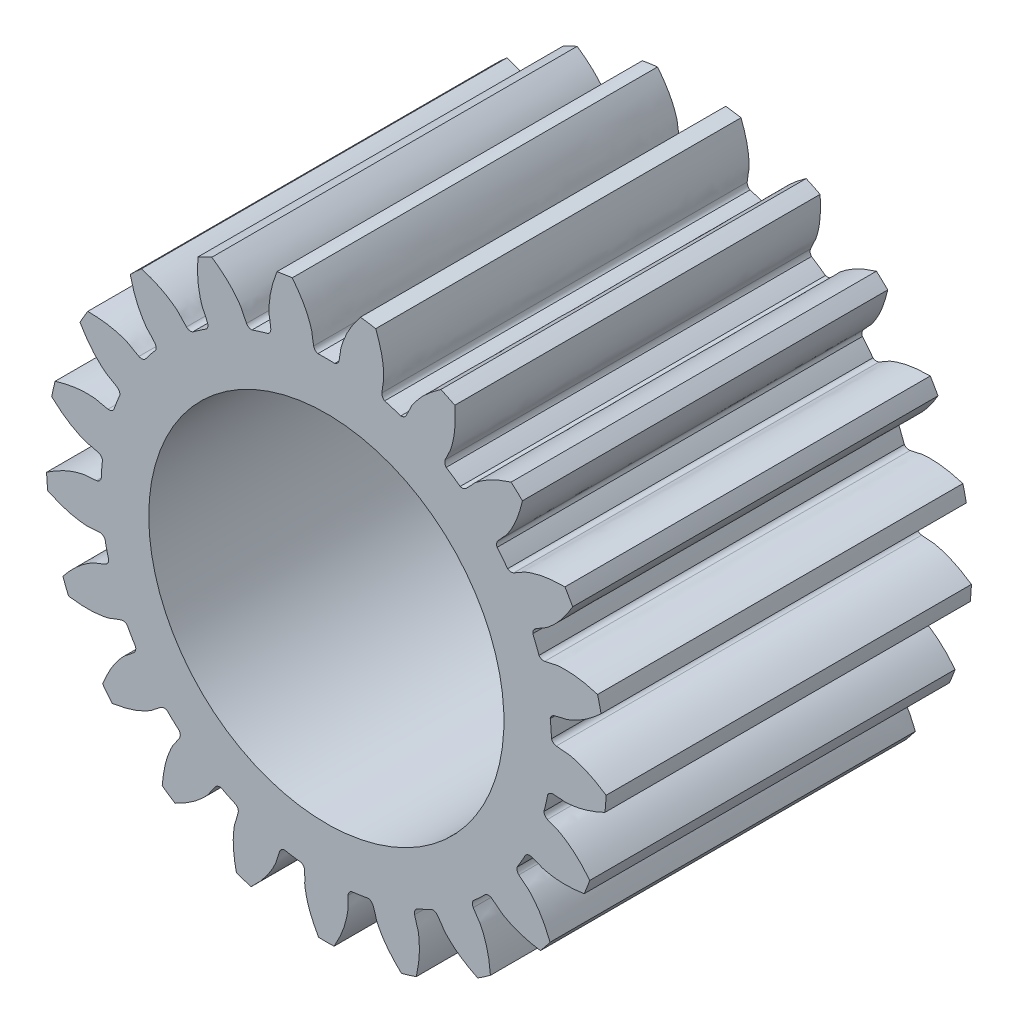
SolidWorks part; units mm, degrees
ref_plane "Front Plane" through (0, 0, 0) normal (0, 0, 1) x (1, 0, 0)
ref_plane "Top Plane" through (0, 0, 0) normal (0, 1, 0) x (1, 0, 0)
ref_plane "Right Plane" through (0, 0, 0) normal (1, 0, 0) x (0, 0, -1)
ref_plane "Plane1" through (0, 0, 19) normal (0, 0, 1) x (1, 0, 0)
sketch "Sketch1" plane through (0, 0, 19) normal (0, 0, 1) x (1, 0, 0)
  arc A0 (6.1126, 17.461) -> (4.7856, 17.8703) centre (0, 0) ccw
  arc A1 (4.7856, 17.8703) -> (4.5626, 18.3266) centre (5.0611, 18.2876) cw
  arc A2 (4.0545, 22.6398) -> (2.7989, 22.8291) centre (0, 0) ccw
  arc A3 (1.042, 18.8573) -> (0.6944, 18.487) centre (0.5542, 18.9669) cw
  arc A4 (0.6944, 18.487) -> (-0.6944, 18.487) centre (0, 0) ccw
  arc A5 (-0.6944, 18.487) -> (-1.042, 18.8573) centre (-0.5542, 18.9669) cw
  arc A6 (-2.7989, 22.8291) -> (-4.0545, 22.6398) centre (0, 0) ccw
  arc A7 (-4.5626, 18.3266) -> (-4.7856, 17.8703) centre (-5.0611, 18.2876) cw
  arc A8 (-4.7856, 17.8703) -> (-6.1126, 17.461) centre (0, 0) ccw
  arc A9 (-6.1126, 17.461) -> (-6.554, 17.7124) centre (-6.1201, 17.9609) cw
  arc A10 (-9.4035, 20.9899) -> (-10.5476, 20.4389) centre (0, 0) ccw
  arc A11 (-9.7617, 16.1676) -> (-9.8404, 15.6658) centre (-10.2266, 15.9834) cw
  arc A12 (-9.8404, 15.6658) -> (-10.9878, 14.8835) centre (0, 0) ccw
  arc A13 (-10.9878, 14.8835) -> (-11.4836, 14.9936) centre (-11.1423, 15.359) cw
  arc A14 (-15.1726, 17.2856) -> (-16.1034, 16.4219) centre (0, 0) ccw
  arc A15 (-14.0935, 12.572) -> (-14.0208, 12.0693) centre (-14.4834, 12.2589) cw
  arc A16 (-14.0208, 12.0693) -> (-14.8866, 10.9836) centre (0, 0) ccw
  arc A17 (-14.8866, 10.9836) -> (-15.3929, 10.9427) centre (-15.1744, 11.3924) cw
  arc A18 (-19.5935, 12.0455) -> (-20.2284, 10.9458) centre (0, 0) ccw
  arc A19 (-17.1731, 7.8593) -> (-16.9554, 7.4004) centre (-17.4533, 7.4452) cw
  arc A20 (-16.9554, 7.4004) -> (-17.4627, 6.1077) centre (0, 0) ccw
  arc A21 (-17.4627, 6.1077) -> (-17.9344, 5.9194) centre (-17.8583, 6.4135) cw
  arc A22 (-22.2735, 5.735) -> (-22.5561, 4.497) centre (0, 0) ccw
  arc A23 (-18.7267, 2.4483) -> (-18.3834, 2.074) centre (-18.8725, 1.97) cw
  arc A24 (-18.3834, 2.074) -> (-18.4872, 0.6891) centre (0, 0) ccw
  arc A25 (-18.4872, 0.6891) -> (-18.8824, 0.3701) centre (-18.9553, 0.8648) cw
  arc A26 (-22.9744, -1.085) -> (-22.8795, -2.3513) centre (0, 0) ccw
  arc A27 (-18.6164, -3.1803) -> (-18.178, -3.4368) centre (-18.6147, -3.6803) cw
  arc A28 (-18.178, -3.4368) -> (-17.8689, -4.7907) centre (0, 0) ccw
  arc A29 (-17.8689, -4.7907) -> (-18.1526, -5.212) centre (-18.3681, -4.7608) cw
  arc A30 (-21.6339, -7.8086) -> (-21.17, -8.9907) centre (0, 0) ccw
  arc A31 (-16.8519, -8.5262) -> (-16.3574, -8.6421) centre (-16.7029, -9.0035) cw
  arc A32 (-16.3574, -8.6421) -> (-15.663, -9.8448) centre (0, 0) ccw
  arc A33 (-15.663, -9.8448) -> (-15.8099, -10.331) centre (-16.1487, -9.9634) cw
  arc A34 (-18.3711, -13.8384) -> (-17.5794, -14.8312) centre (0, 0) ccw
  arc A35 (-13.5901, -13.1146) -> (-13.0833, -13.0796) centre (-13.307, -13.5268) cw
  arc A36 (-13.0833, -13.0796) -> (-12.0653, -14.0242) centre (0, 0) ccw
  arc A37 (-12.0653, -14.0242) -> (-12.0624, -14.5321) centre (-12.4945, -14.2807) cw
  arc A38 (-13.476, -18.6386) -> (-12.4268, -19.3539) centre (0, 0) ccw
  arc A39 (-9.1207, -16.5377) -> (-8.6468, -16.3549) centre (-8.7287, -16.8481) cw
  arc A40 (-8.6468, -16.3549) -> (-7.3956, -16.9575) centre (0, 0) ccw
  arc A41 (-7.3956, -16.9575) -> (-7.2431, -17.4419) centre (-7.7301, -17.329) cw
  arc A42 (-7.3835, -21.7827) -> (-6.1701, -22.1569) centre (0, 0) ccw
  arc A43 (-3.8409, -18.4914) -> (-3.4419, -18.177) centre (-3.3748, -18.6725) cw
  arc A44 (-3.4419, -18.177) -> (-2.0687, -18.384) centre (0, 0) ccw
  arc A45 (-2.0687, -18.384) -> (-1.7802, -18.802) centre (-2.2789, -18.8377) cw
  arc A46 (-0.6349, -22.9912) -> (0.6349, -22.9912) centre (0, 0) ccw
  arc A47 (1.7802, -18.802) -> (2.0687, -18.384) centre (2.2789, -18.8377) cw
  arc A48 (2.0687, -18.384) -> (3.4419, -18.177) centre (0, 0) ccw
  arc A49 (3.4419, -18.177) -> (3.8409, -18.4914) centre (3.3748, -18.6725) cw
  arc A50 (6.1701, -22.1569) -> (7.3835, -21.7827) centre (0, 0) ccw
  arc A51 (7.2431, -17.4419) -> (7.3956, -16.9575) centre (7.7301, -17.329) cw
  arc A52 (7.3956, -16.9575) -> (8.6468, -16.3549) centre (0, 0) ccw
  arc A53 (8.6468, -16.3549) -> (9.1207, -16.5377) centre (8.7287, -16.8481) cw
  arc A54 (12.4268, -19.3539) -> (13.476, -18.6386) centre (0, 0) ccw
  arc A55 (12.0624, -14.5321) -> (12.0653, -14.0242) centre (12.4945, -14.2807) cw
  arc A56 (12.0653, -14.0242) -> (13.0833, -13.0796) centre (0, 0) ccw
  arc A57 (13.0833, -13.0796) -> (13.5901, -13.1146) centre (13.307, -13.5268) cw
  arc A58 (17.5794, -14.8312) -> (18.3711, -13.8384) centre (0, 0) ccw
  arc A59 (15.8099, -10.331) -> (15.663, -9.8448) centre (16.1487, -9.9634) cw
  arc A60 (15.663, -9.8448) -> (16.3574, -8.6421) centre (0, 0) ccw
  arc A61 (16.3574, -8.6421) -> (16.8519, -8.5262) centre (16.7029, -9.0035) cw
  arc A62 (21.17, -8.9907) -> (21.6339, -7.8086) centre (0, 0) ccw
  arc A63 (18.1526, -5.212) -> (17.8689, -4.7907) centre (18.3681, -4.7608) cw
  arc A64 (17.8689, -4.7907) -> (18.178, -3.4368) centre (0, 0) ccw
  arc A65 (18.178, -3.4368) -> (18.6164, -3.1803) centre (18.6147, -3.6803) cw
  arc A66 (22.8795, -2.3513) -> (22.9744, -1.085) centre (0, 0) ccw
  arc A67 (18.8824, 0.3701) -> (18.4872, 0.6891) centre (18.9553, 0.8648) cw
  arc A68 (18.4872, 0.6891) -> (18.3834, 2.074) centre (0, 0) ccw
  arc A69 (18.3834, 2.074) -> (18.7267, 2.4483) centre (18.8725, 1.97) cw
  arc A70 (22.5561, 4.497) -> (22.2735, 5.735) centre (0, 0) ccw
  arc A71 (17.9344, 5.9194) -> (17.4627, 6.1077) centre (17.8583, 6.4135) cw
  arc A72 (17.4627, 6.1077) -> (16.9554, 7.4004) centre (0, 0) ccw
  arc A73 (16.9554, 7.4004) -> (17.1731, 7.8593) centre (17.4533, 7.4452) cw
  arc A74 (20.2284, 10.9458) -> (19.5935, 12.0455) centre (0, 0) ccw
  arc A75 (15.3929, 10.9427) -> (14.8866, 10.9836) centre (15.1744, 11.3924) cw
  arc A76 (14.8866, 10.9836) -> (14.0208, 12.0693) centre (0, 0) ccw
  arc A77 (14.0208, 12.0693) -> (14.0935, 12.572) centre (14.4834, 12.2589) cw
  arc A78 (16.1034, 16.4219) -> (15.1726, 17.2856) centre (0, 0) ccw
  arc A79 (11.4836, 14.9936) -> (10.9878, 14.8835) centre (11.1423, 15.359) cw
  arc A80 (10.9878, 14.8835) -> (9.8404, 15.6658) centre (0, 0) ccw
  arc A81 (9.8404, 15.6658) -> (9.7617, 16.1676) centre (10.2266, 15.9834) cw
  arc A82 (10.5476, 20.4389) -> (9.4035, 20.9899) centre (0, 0) ccw
  arc A83 (6.554, 17.7124) -> (6.1126, 17.461) centre (6.1201, 17.9609) cw
  circle A84 centre (0, 0) radius 5
  spline S0 degree 3 poles (4.5626, 18.3266) (4.6069, 18.8931) (4.7106, 19.1585) (4.7118, 19.7328) (4.6722, 20.4567) (4.4602, 21.5102) (4.2123, 22.2245) (4.0545, 22.6398) knots 0 0 0 0 0.147601 0.232682 0.408923 0.684333 1 1 1 1
  spline S1 degree 3 poles (1.042, 18.8573) (1.1666, 19.4117) (1.1458, 19.6958) (1.3139, 20.2449) (1.5651, 20.925) (2.0782, 21.8693) (2.5256, 22.4787) (2.7989, 22.8291) knots 0 0 0 0 0.147601 0.232682 0.408923 0.684333 1 1 1 1
  spline S2 degree 3 poles (-1.042, 18.8573) (-1.1666, 19.4117) (-1.1458, 19.6958) (-1.3139, 20.2449) (-1.5651, 20.925) (-2.0782, 21.8693) (-2.5256, 22.4787) (-2.7989, 22.8291) knots 0 0 0 0 0.147601 0.232682 0.408923 0.684333 1 1 1 1
  spline S3 degree 3 poles (-4.5626, 18.3266) (-4.6069, 18.8931) (-4.7106, 19.1585) (-4.7118, 19.7328) (-4.6722, 20.4567) (-4.4602, 21.5102) (-4.2123, 22.2245) (-4.0545, 22.6398) knots 0 0 0 0 0.147601 0.232682 0.408923 0.684333 1 1 1 1
  spline S4 degree 3 poles (-6.554, 17.7124) (-6.8364, 18.2054) (-6.9003, 18.4831) (-7.2228, 18.9582) (-7.6633, 19.5341) (-8.432, 20.2851) (-9.0391, 20.7356) (-9.4035, 20.9899) knots 0 0 0 0 0.147601 0.232682 0.408923 0.684333 1 1 1 1
  spline S5 degree 3 poles (-9.7617, 16.1676) (-9.9711, 16.6958) (-10.1484, 16.9189) (-10.3188, 17.4673) (-10.4944, 18.1707) (-10.6023, 19.2399) (-10.576, 19.9955) (-10.5476, 20.4389) knots 0 0 0 0 0.147601 0.232682 0.408923 0.684333 1 1 1 1
  spline S6 degree 3 poles (-11.4836, 14.9936) (-11.8989, 15.3815) (-12.0417, 15.628) (-12.4899, 15.987) (-13.0806, 16.4074) (-14.0365, 16.8985) (-14.7495, 17.1501) (-15.1726, 17.2856) knots 0 0 0 0 0.147601 0.232682 0.408923 0.684333 1 1 1 1
  spline S7 degree 3 poles (-14.0935, 12.572) (-14.4493, 13.015) (-14.6844, 13.176) (-15.0089, 13.6497) (-15.384, 14.2702) (-15.8023, 15.2601) (-15.9999, 15.9898) (-16.1034, 16.4219) knots 0 0 0 0 0.147601 0.232682 0.408923 0.684333 1 1 1 1
  spline S8 degree 3 poles (-15.3929, 10.9427) (-15.904, 11.1909) (-16.1132, 11.3844) (-16.6473, 11.5953) (-17.3357, 11.8229) (-18.3938, 12.0105) (-19.1493, 12.0407) (-19.5935, 12.0455) knots 0 0 0 0 0.147601 0.232682 0.408923 0.684333 1 1 1 1
  spline S9 degree 3 poles (-17.1731, 7.8593) (-17.6436, 8.1778) (-17.9157, 8.2623) (-18.3654, 8.6193) (-18.9068, 9.1017) (-19.5983, 9.9243) (-20.0022, 10.5634) (-20.2284, 10.9458) knots 0 0 0 0 0.147601 0.232682 0.408923 0.684333 1 1 1 1
  spline S10 degree 3 poles (-17.9344, 5.9194) (-18.496, 6.006) (-18.7529, 6.1291) (-19.3255, 6.1733) (-20.0504, 6.1879) (-21.1168, 6.0552) (-21.8476, 5.8614) (-22.2735, 5.735) knots 0 0 0 0 0.147601 0.232682 0.408923 0.684333 1 1 1 1
  spline S11 degree 3 poles (-18.7267, 2.4483) (-19.2702, 2.6139) (-19.5551, 2.6144) (-20.0901, 2.8231) (-20.7496, 3.1244) (-21.6528, 3.7067) (-22.2271, 4.1984) (-22.5561, 4.497) knots 0 0 0 0 0.147601 0.232682 0.408923 0.684333 1 1 1 1
  spline S12 degree 3 poles (-18.8824, 0.3701) (-19.4446, 0.2873) (-19.7264, 0.3293) (-20.2865, 0.2027) (-20.9835, 0.003) (-21.9634, -0.4381) (-22.6046, -0.8387) (-22.9744, -1.085) knots 0 0 0 0 0.147601 0.232682 0.408923 0.684333 1 1 1 1
  spline S13 degree 3 poles (-18.6164, -3.1803) (-19.1846, -3.1822) (-19.457, -3.2657) (-20.0297, -3.224) (-20.7487, -3.1304) (-21.7834, -2.8403) (-22.4771, -2.5397) (-22.8795, -2.3513) knots 0 0 0 0 0.147601 0.232682 0.408923 0.684333 1 1 1 1
  spline S14 degree 3 poles (-18.1526, -5.212) (-18.6654, -5.4568) (-18.9471, -5.4998) (-19.445, -5.7858) (-20.0521, -6.1821) (-20.8585, -6.8925) (-21.3531, -7.4643) (-21.6339, -7.8086) knots 0 0 0 0 0.147601 0.232682 0.408923 0.684333 1 1 1 1
  spline S15 degree 3 poles (-16.8519, -8.5262) (-17.3943, -8.6956) (-17.63, -8.8557) (-18.1895, -8.9846) (-18.9042, -9.1071) (-19.9784, -9.1348) (-20.7299, -9.0521) (-21.17, -8.9907) knots 0 0 0 0 0.147601 0.232682 0.408923 0.684333 1 1 1 1
  spline S16 degree 3 poles (-15.8099, -10.331) (-16.2277, -10.7161) (-16.4842, -10.8402) (-16.8757, -11.2603) (-17.3391, -11.8179) (-17.9002, -12.7344) (-18.2044, -13.4266) (-18.3711, -13.8384) knots 0 0 0 0 0.147601 0.232682 0.408923 0.684333 1 1 1 1
  spline S17 degree 3 poles (-13.5901, -13.1146) (-14.0585, -13.4363) (-14.2365, -13.6587) (-14.7332, -13.9469) (-15.3799, -14.2746) (-16.3983, -14.6178) (-17.1408, -14.7602) (-17.5794, -14.8312) knots 0 0 0 0 0.147601 0.232682 0.408923 0.684333 1 1 1 1
  spline S18 degree 3 poles (-12.0624, -14.5321) (-12.3481, -15.0232) (-12.5567, -15.2174) (-12.8069, -15.7342) (-13.0854, -16.4037) (-13.3514, -17.4449) (-13.438, -18.1959) (-13.476, -18.6386) knots 0 0 0 0 0.147601 0.232682 0.408923 0.684333 1 1 1 1
  spline S19 degree 3 poles (-9.1207, -16.5377) (-9.4735, -16.9832) (-9.578, -17.2482) (-9.9677, -17.67) (-10.4891, -18.1737) (-11.3611, -18.8018) (-12.0286, -19.1568) (-12.4268, -19.3539) knots 0 0 0 0 0.147601 0.232682 0.408923 0.684333 1 1 1 1
  spline S20 degree 3 poles (-7.2431, -17.4419) (-7.3714, -17.9955) (-7.5134, -18.2425) (-7.6002, -18.8101) (-7.6689, -19.5319) (-7.6163, -20.6052) (-7.4777, -21.3485) (-7.3835, -21.7827) knots 0 0 0 0 0.147601 0.232682 0.408923 0.684333 1 1 1 1
  spline S21 degree 3 poles (-3.8409, -18.4914) (-4.0467, -19.021) (-4.0685, -19.3051) (-4.3165, -19.823) (-4.6663, -20.4581) (-5.3144, -21.3153) (-5.8477, -21.8512) (-6.1701, -22.1569) knots 0 0 0 0 0.147601 0.232682 0.408923 0.684333 1 1 1 1
  spline S22 degree 3 poles (-1.7802, -18.802) (-1.7396, -19.3687) (-1.8025, -19.6466) (-1.7182, -20.2146) (-1.5711, -20.9246) (-1.2044, -21.9347) (-0.8529, -22.6041) (-0.6349, -22.9912) knots 0 0 0 0 0.147601 0.232682 0.408923 0.684333 1 1 1 1
  spline S23 degree 3 poles (1.7802, -18.802) (1.7396, -19.3687) (1.8025, -19.6466) (1.7182, -20.2146) (1.5711, -20.9246) (1.2044, -21.9347) (0.8529, -22.6041) (0.6349, -22.9912) knots 0 0 0 0 0.147601 0.232682 0.408923 0.684333 1 1 1 1
  spline S24 degree 3 poles (3.8409, -18.4914) (4.0467, -19.021) (4.0685, -19.3051) (4.3165, -19.823) (4.6663, -20.4581) (5.3144, -21.3153) (5.8477, -21.8512) (6.1701, -22.1569) knots 0 0 0 0 0.147601 0.232682 0.408923 0.684333 1 1 1 1
  spline S25 degree 3 poles (7.2431, -17.4419) (7.3714, -17.9955) (7.5134, -18.2425) (7.6002, -18.8101) (7.6689, -19.5319) (7.6163, -20.6052) (7.4777, -21.3485) (7.3835, -21.7827) knots 0 0 0 0 0.147601 0.232682 0.408923 0.684333 1 1 1 1
  spline S26 degree 3 poles (9.1207, -16.5377) (9.4735, -16.9832) (9.578, -17.2482) (9.9677, -17.67) (10.4891, -18.1737) (11.3611, -18.8018) (12.0286, -19.1568) (12.4268, -19.3539) knots 0 0 0 0 0.147601 0.232682 0.408923 0.684333 1 1 1 1
  spline S27 degree 3 poles (12.0624, -14.5321) (12.3481, -15.0232) (12.5567, -15.2174) (12.8069, -15.7342) (13.0854, -16.4037) (13.3514, -17.4449) (13.438, -18.1959) (13.476, -18.6386) knots 0 0 0 0 0.147601 0.232682 0.408923 0.684333 1 1 1 1
  spline S28 degree 3 poles (13.5901, -13.1146) (14.0585, -13.4363) (14.2365, -13.6587) (14.7332, -13.9469) (15.3799, -14.2746) (16.3983, -14.6178) (17.1408, -14.7602) (17.5794, -14.8312) knots 0 0 0 0 0.147601 0.232682 0.408923 0.684333 1 1 1 1
  spline S29 degree 3 poles (15.8099, -10.331) (16.2277, -10.7161) (16.4842, -10.8402) (16.8757, -11.2603) (17.3391, -11.8179) (17.9002, -12.7344) (18.2044, -13.4266) (18.3711, -13.8384) knots 0 0 0 0 0.147601 0.232682 0.408923 0.684333 1 1 1 1
  spline S30 degree 3 poles (16.8519, -8.5262) (17.3943, -8.6956) (17.63, -8.8557) (18.1895, -8.9846) (18.9042, -9.1071) (19.9784, -9.1348) (20.7299, -9.0521) (21.17, -8.9907) knots 0 0 0 0 0.147601 0.232682 0.408923 0.684333 1 1 1 1
  spline S31 degree 3 poles (18.1526, -5.212) (18.6654, -5.4568) (18.9471, -5.4998) (19.445, -5.7858) (20.0521, -6.1821) (20.8585, -6.8925) (21.3531, -7.4643) (21.6339, -7.8086) knots 0 0 0 0 0.147601 0.232682 0.408923 0.684333 1 1 1 1
  spline S32 degree 3 poles (18.6164, -3.1803) (19.1846, -3.1822) (19.457, -3.2657) (20.0297, -3.224) (20.7487, -3.1304) (21.7834, -2.8403) (22.4771, -2.5397) (22.8795, -2.3513) knots 0 0 0 0 0.147601 0.232682 0.408923 0.684333 1 1 1 1
  spline S33 degree 3 poles (18.8824, 0.3701) (19.4446, 0.2873) (19.7264, 0.3293) (20.2865, 0.2027) (20.9835, 0.003) (21.9634, -0.4381) (22.6046, -0.8387) (22.9744, -1.085) knots 0 0 0 0 0.147601 0.232682 0.408923 0.684333 1 1 1 1
  spline S34 degree 3 poles (18.7267, 2.4483) (19.2702, 2.6139) (19.5551, 2.6144) (20.0901, 2.8231) (20.7496, 3.1244) (21.6528, 3.7067) (22.2271, 4.1984) (22.5561, 4.497) knots 0 0 0 0 0.147601 0.232682 0.408923 0.684333 1 1 1 1
  spline S35 degree 3 poles (17.9344, 5.9194) (18.496, 6.006) (18.7529, 6.1291) (19.3255, 6.1733) (20.0504, 6.1879) (21.1168, 6.0552) (21.8476, 5.8614) (22.2735, 5.735) knots 0 0 0 0 0.147601 0.232682 0.408923 0.684333 1 1 1 1
  spline S36 degree 3 poles (17.1731, 7.8593) (17.6436, 8.1778) (17.9157, 8.2623) (18.3654, 8.6193) (18.9068, 9.1017) (19.5983, 9.9243) (20.0022, 10.5634) (20.2284, 10.9458) knots 0 0 0 0 0.147601 0.232682 0.408923 0.684333 1 1 1 1
  spline S37 degree 3 poles (15.3929, 10.9427) (15.904, 11.1909) (16.1132, 11.3844) (16.6473, 11.5953) (17.3357, 11.8229) (18.3938, 12.0105) (19.1493, 12.0407) (19.5935, 12.0455) knots 0 0 0 0 0.147601 0.232682 0.408923 0.684333 1 1 1 1
  spline S38 degree 3 poles (14.0935, 12.572) (14.4493, 13.015) (14.6844, 13.176) (15.0089, 13.6497) (15.384, 14.2702) (15.8023, 15.2601) (15.9999, 15.9898) (16.1034, 16.4219) knots 0 0 0 0 0.147601 0.232682 0.408923 0.684333 1 1 1 1
  spline S39 degree 3 poles (11.4836, 14.9936) (11.8989, 15.3815) (12.0417, 15.628) (12.4899, 15.987) (13.0806, 16.4074) (14.0365, 16.8985) (14.7495, 17.1501) (15.1726, 17.2856) knots 0 0 0 0 0.147601 0.232682 0.408923 0.684333 1 1 1 1
  spline S40 degree 3 poles (9.7617, 16.1676) (9.9711, 16.6958) (10.1484, 16.9189) (10.3188, 17.4673) (10.4944, 18.1707) (10.6023, 19.2399) (10.576, 19.9955) (10.5476, 20.4389) knots 0 0 0 0 0.147601 0.232682 0.408923 0.684333 1 1 1 1
  spline S41 degree 3 poles (6.554, 17.7124) (6.8364, 18.2054) (6.9003, 18.4831) (7.2228, 18.9582) (7.6633, 19.5341) (8.432, 20.2851) (9.0391, 20.7356) (9.4035, 20.9899) knots 0 0 0 0 0.147601 0.232682 0.408923 0.684333 1 1 1 1
extrude "Boss-Extrude1" add sketch "Sketch1" against normal blind 30
scale "Scale3" scale about centroid uniform scaling yes scale factor 0.3
sketch "Sketch2" plane through (0, 0, 19) normal (0, 0, 1) x (1, 0, 0)
  circle A0 centre (0, 0) radius 4.375
  point P2 (0, 0)
  dimension "D1" = 8.75
extrude "Cut-Extrude1" cut sketch "Sketch2" against normal up to next
